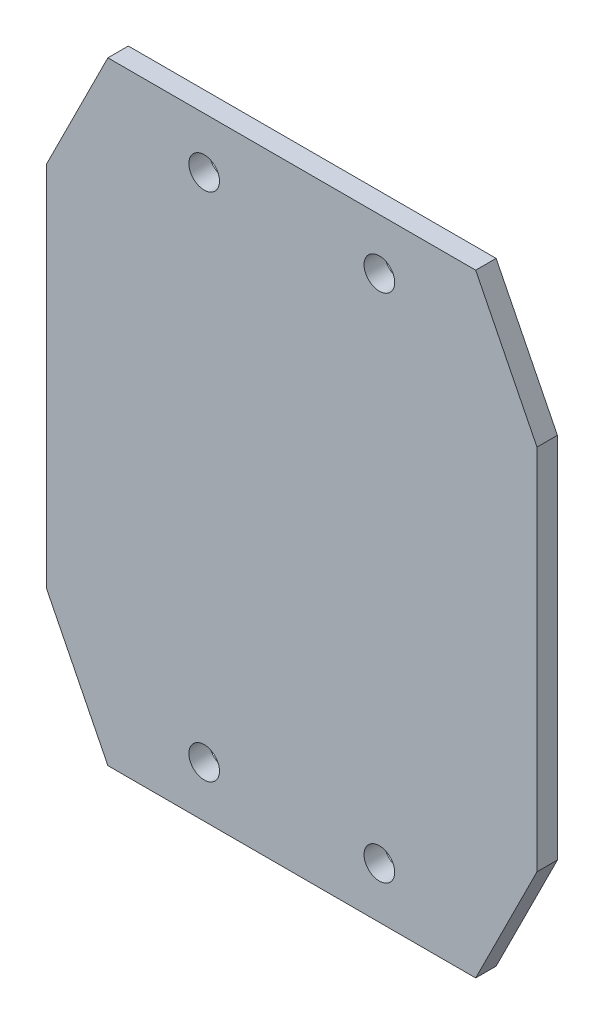
SolidWorks part; units mm, degrees
ref_plane "Front" through (0, 0, 0) normal (0, 0, 1) x (1, 0, 0)
ref_plane "Top" through (0, 0, 0) normal (0, 1, 0) x (1, 0, 0)
ref_plane "Right" through (0, 0, 0) normal (1, 0, 0) x (0, 0, -1)
sketch "Sketch2" plane through (0, 0, 0) normal (0, 0, 1) x (1, 0, 0)
  line L0 (0, 0) -> (0, 150) construction
  line L1 (-125, -150) -> (125, -150) construction
  line L2 (-125, -150) -> (-125, 150) construction
  line L3 (-125, 150) -> (125, 150) construction
  line L4 (125, -150) -> (125, 150) construction
  line L5 (-125, -150) -> (125, 150) construction
  line L6 (-125, 150) -> (125, -150) construction
  line L7 (-35, -150) -> (35, -150) construction
  line L8 (-35, -150) -> (-35, 150) construction
  line L9 (-35, 150) -> (35, 150) construction
  line L10 (35, -150) -> (35, 150) construction
  line L11 (-35, -150) -> (35, 150) construction
  line L12 (-35, 150) -> (35, -150) construction
  line L13 (0, 0) -> (0, -150) construction
  line L14 (-42.8625, 125) -> (42.8625, 125) construction
  line L15 (-42.8625, -125) -> (42.8625, -125) construction
  line L16 (0, 125) -> (0, -125) construction
  line L17 (-90, 150) -> (90, 150)
  line L18 (90, 150) -> (120, 90)
  line L19 (120, 90) -> (120, -90)
  line L20 (120, -90) -> (90, -150)
  line L22 (-90, -150) -> (-120, -90)
  line L23 (-120, -90) -> (-120, 90)
  line L24 (-120, 90) -> (-90, 150)
  line L25 (90, -150) -> (-90, -150)
  line L26 (-120, 0) -> (120, 0) construction
  circle A0 centre (0, 0) radius 105 construction
  circle A1 centre (42.8625, 125) radius 7.5
  circle A2 centre (-42.8625, 125) radius 7.5
  circle A3 centre (-42.8625, -125) radius 7.5
  circle A4 centre (42.8625, -125) radius 7.5
  point P17 (0, -125)
  point P18 (0, 125)
  point P26 (0, 0)
  point P34 (0, -150)
  point P35 (0, 150)
  point P38 (0, 0)
  dimension "D1" = 210
  dimension "D7" = 15
  dimension "D8" = 15
  dimension "D9" = 15
  dimension "D10" = 15
  dimension "D2" = 250
  dimension "D3" = 300
  dimension "D4" = 70
  dimension "D5" = 85.725
  dimension "D6" = 85.725
  dimension "D11" = 250
  dimension "D12" = 180
  dimension "D13" = 180
  dimension "D14" = 180
  dimension "D15" = 180
  dimension "D16" = 25
  dimension "D17" = 25
  dimension "D18" = 240
extrude "Boss-Extrude1" add sketch "Sketch2" along normal blind 10
sketch "Sketch3" plane through (0, 0, 0) normal (0, 1, 0) x (1, 0, 0)
  line L0 (0, 0) -> (0, 200) construction
  dimension "D1" = 200
